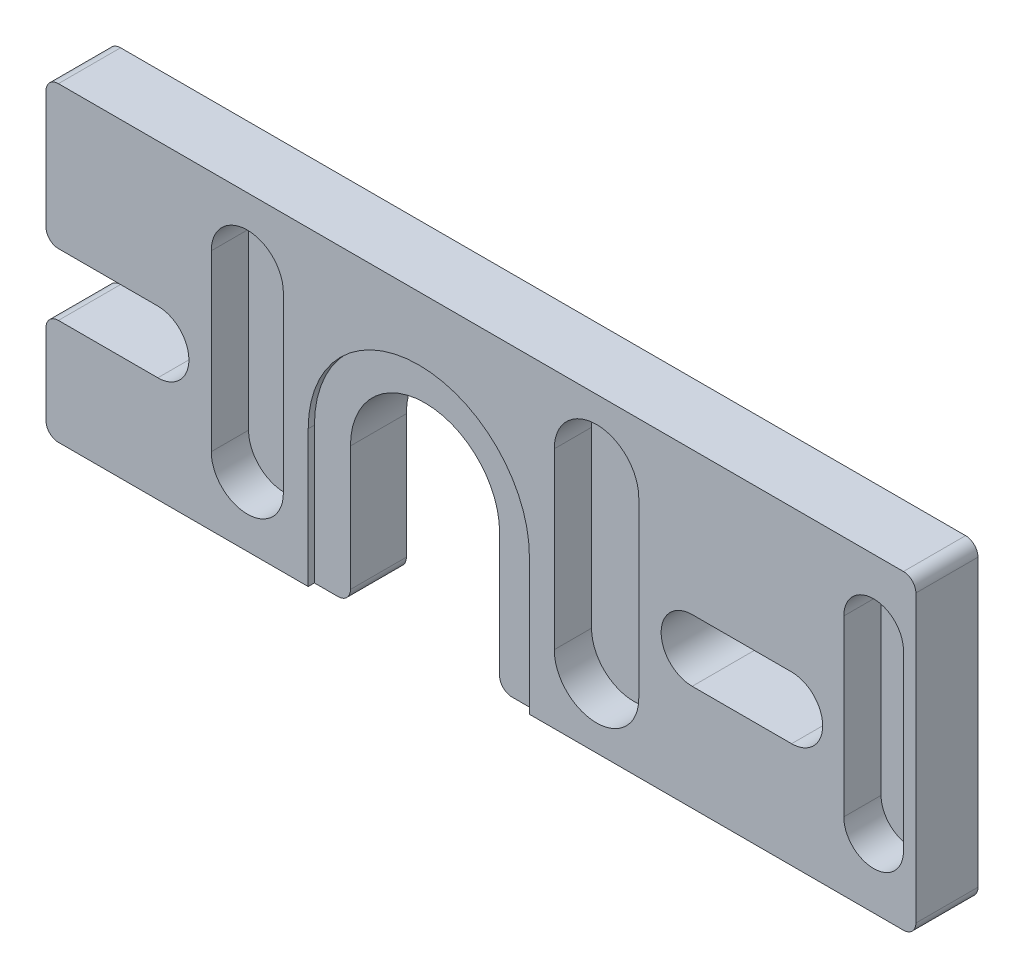
SolidWorks part; units mm, degrees
material "6061-T6 (SS)"
ref_plane "Front Plane" through (0, 0, 0) normal (0, 0, 1) x (1, 0, 0)
ref_plane "Top Plane" through (0, 0, 0) normal (0, 1, 0) x (1, 0, 0)
ref_plane "Right Plane" through (0, 0, 0) normal (1, 0, 0) x (0, 0, -1)
ref_plane "Plane1" through (0, 0, 5) normal (0, 0, 1) x (1, 0, 0)
sketch "Sketch1" plane through (0, 0, 5) normal (0, 0, 1) x (1, 0, 0)
  line L0 (0, 25) -> (0, 0)
  line L1 (0, 0) -> (70, 0)
  line L2 (70, 0) -> (70, 25)
  line L3 (70, 25) -> (0, 25)
extrude "Boss-Extrude1" add sketch "Sketch1" against normal blind 5
sketch "Sketch2" plane through (0, 0, 5) normal (0, 0, 1) x (1, 0, 0)
  line L0 (38.9, 0) -> (38.9, 11)
  line L1 (21.1, 11) -> (21.1, 0)
  line L2 (21.1, 0) -> (38.9, 0)
  arc A0 (38.9, 11) -> (21.1, 11) centre (30, 11) ccw
extrude "Cut-Extrude1" cut sketch "Sketch2" against normal blind 0.5
sketch "Sketch3" plane through (0, 0, 0) normal (0, 0, -1) x (-1, 0, 0)
  line L0 (-36, 0) -> (-24, 0)
  line L1 (-24, 0) -> (-24, 11)
  line L2 (-36, 11) -> (-36, 0)
  arc A0 (-24, 11) -> (-36, 11) centre (-30, 11) ccw
extrude "Cut-Extrude2" cut sketch "Sketch3" against normal through all
sketch "Sketch4" plane through (0, 0, 0) normal (0, 0, -1) x (-1, 0, 0)
  line L0 (0, 8.5) -> (0, 13.5)
  line L1 (0, 13.5) -> (-9, 13.5)
  line L2 (-9, 8.5) -> (0, 8.5)
  arc A0 (-9, 13.5) -> (-9, 8.5) centre (-9, 11) ccw
extrude "Cut-Extrude3" cut sketch "Sketch4" against normal through all
sketch "Sketch5" plane through (0, 0, 0) normal (0, 0, -1) x (-1, 0, 0)
  line L0 (-52, 13.5) -> (-60, 13.5)
  line L1 (-60, 8.5) -> (-52, 8.5)
  arc A0 (-60, 13.5) -> (-60, 8.5) centre (-60, 11) ccw
  arc A1 (-52, 8.5) -> (-52, 13.5) centre (-52, 11) ccw
extrude "Cut-Extrude4" cut sketch "Sketch5" against normal through all
sketch "Sketch6" plane through (0, 0, 5) normal (0, 0, 1) x (1, 0, 0)
  line L0 (69, 5.5) -> (69, 19.5)
  line L1 (64.2, 19.5) -> (64.2, 5.5)
  arc A0 (64.2, 5.5) -> (69, 5.5) centre (66.6, 5.5) ccw
  arc A1 (69, 19.5) -> (64.2, 19.5) centre (66.6, 19.5) ccw
extrude "Cut-Extrude5" cut sketch "Sketch6" against normal blind 3
sketch "Sketch7" plane through (0, 0, 5) normal (0, 0, 1) x (1, 0, 0)
  line L0 (47.7, 5.5) -> (47.7, 19.5)
  line L1 (40.9, 19.5) -> (40.9, 5.5)
  arc A0 (40.9, 5.5) -> (47.7, 5.5) centre (44.3, 5.5) ccw
  arc A1 (47.7, 19.5) -> (40.9, 19.5) centre (44.3, 19.5) ccw
extrude "Cut-Extrude6" cut sketch "Sketch7" against normal blind 3
sketch "Sketch8" plane through (0, 0, 5) normal (0, 0, 1) x (1, 0, 0)
  line L0 (19.1, 5.5) -> (19.1, 19.5)
  line L1 (13.3, 19.5) -> (13.3, 5.5)
  arc A0 (13.3, 5.5) -> (19.1, 5.5) centre (16.2, 5.5) ccw
  arc A1 (19.1, 19.5) -> (13.3, 19.5) centre (16.2, 19.5) ccw
extrude "Cut-Extrude7" cut sketch "Sketch8" against normal blind 3
fillet "Fillet1" radius 1 8 edges at (24, 0, 2.25) (70, 0, 2.5) (70, 25, 2.5) (0, 8.5, 2.5) (36, 0, 2.25) (0, 13.5, 2.5) (0, 0, 2.5) (0, 25, 2.5)
